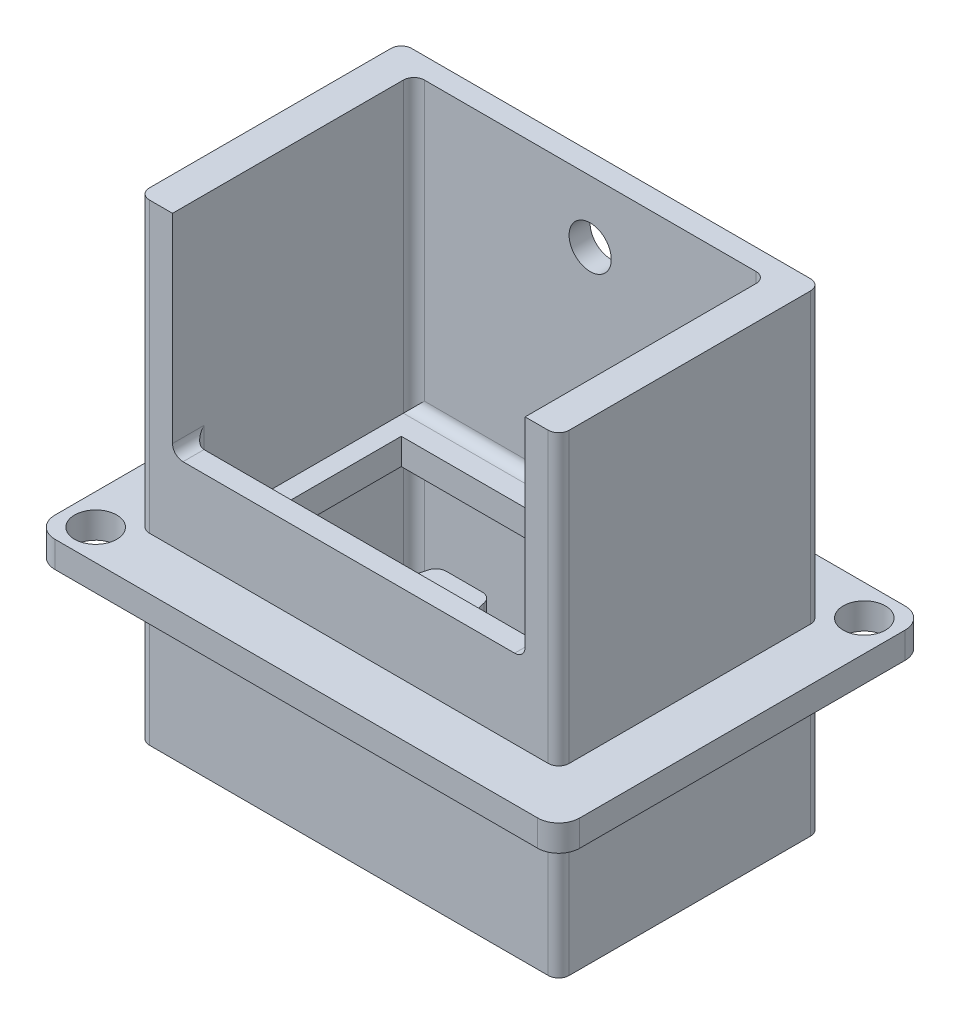
SolidWorks part; units mm, degrees
ref_plane "Front Plane" through (0, 0, 0) normal (0, 0, 1) x (1, 0, 0)
ref_plane "Top Plane" through (0, 0, 0) normal (0, 1, 0) x (1, 0, 0)
ref_plane "Right Plane" through (0, 0, 0) normal (1, 0, 0) x (0, 0, -1)
sketch "Sketch1" plane through (0, 0, 0) normal (0, 1, 0) x (1, 0, 0)
  line L0 (0, 22.225) -> (0, -22.225) construction
  line L1 (-31.75, -22.225) -> (31.75, -22.225)
  line L2 (-31.75, -22.225) -> (-31.75, 22.225)
  line L3 (-31.75, 22.225) -> (31.75, 22.225)
  line L4 (31.75, -22.225) -> (31.75, 22.225)
  line L5 (-31.75, -22.225) -> (31.75, 22.225) construction
  line L6 (-31.75, 22.225) -> (31.75, -22.225) construction
  line L7 (-11.5843, -9.525) -> (-11.176, -9.525)
  line L8 (-19.05, -4.0146) -> (-19.05, 9.525)
  line L9 (-19.05, 9.525) -> (19.05, 9.525)
  line L10 (19.05, -4.0146) -> (19.05, 9.525)
  line L11 (-19.05, -9.525) -> (19.05, 9.525) construction
  line L12 (-19.05, 9.525) -> (19.05, -9.525) construction
  line L13 (3.302, 9.525) -> (3.302, -9.525) construction
  line L14 (-3.302, 9.525) -> (-3.302, -9.525) construction
  line L15 (-19.05, 1.143) -> (19.05, 1.143) construction
  line L16 (-3.302, -1.905) -> (3.302, -1.905)
  line L17 (-11.176, 9.525) -> (-11.176, -9.525) construction
  line L18 (11.176, 9.525) -> (11.176, -9.525) construction
  line L20 (11.176, -9.525) -> (13.6071, -9.525)
  arc A1 (3.302, -1.905) -> (19.05, -4.0146) centre (11.3802, -1.4358) ccw
  arc A2 (-19.05, -4.0146) -> (-3.302, -1.905) centre (-11.3802, -1.4358) ccw
  point P0 (0, 0)
  point P6 (0, 0)
  point P25 (-11.176, 1.143)
  dimension "D1" = 38.1
  dimension "D2" = 19.05
  dimension "D3" = 12.7
  dimension "D4" = 12.7
  dimension "D5" = 15.748
  dimension "D6" = 15.748
  dimension "D7" = 10.668
  dimension "D8" = 11.43
  dimension "D9" = 7.874
  dimension "D10" = 7.874
extrude "Boss-Extrude1" add sketch "Sketch1" along normal blind 3.175
fillet "Fillet3" radius 2.54 4 edges at (31.75, 1.5875, -22.225) (31.75, 1.5875, 22.225) (-31.75, 1.5875, 22.225) (-31.75, 1.5875, -22.225)
sketch "Sketch3" plane through (0, 0, 0) normal (0, -1, 0) x (1, 0, 0)
  line L0 (0, -22.225) -> (0, 22.225) construction
  line L1 (-29.21, -22.225) -> (29.21, -22.225) construction
  line L2 (-29.21, 22.225) -> (29.21, 22.225) construction
  line L3 (31.75, 0) -> (-31.75, 0) construction
  line L4 (31.75, 19.685) -> (31.75, -19.685) construction
  line L5 (-31.75, 19.685) -> (-31.75, -19.685) construction
  line L7 (25.4, 15.875) -> (-25.4, 15.875)
  line L8 (25.4, 15.875) -> (25.4, -15.875)
  line L9 (25.4, -15.875) -> (-25.4, -15.875)
  line L10 (-25.4, 15.875) -> (-25.4, -15.875)
  line L11 (25.4, 15.875) -> (-25.4, -15.875) construction
  line L12 (25.4, -15.875) -> (-25.4, 15.875) construction
  line L13 (21.336, 13.335) -> (-21.336, 13.335)
  line L14 (21.336, 13.335) -> (21.336, -13.335)
  line L15 (21.336, -13.335) -> (-21.336, -13.335)
  line L16 (-21.336, 13.335) -> (-21.336, -13.335)
  line L17 (21.336, 13.335) -> (-21.336, -13.335) construction
  line L18 (21.336, -13.335) -> (-21.336, 13.335) construction
  point P12 (0, 0)
  point P17 (0, 0)
  dimension "D1" = 6.35
  dimension "D2" = 6.35
  dimension "D3" = 2.54
extrude "Boss-Extrude3" add sketch "Sketch3" along normal blind 19.05 and the other way blind 38.1
fillet "Fillet4" radius 1.27 12 edges at (0, 0, 13.335) (-21.336, 0, 0) (0, 0, -13.335) (21.336, 0, 0) (21.336, -9.525, 13.335) (-21.336, -9.525, 13.335) (-21.336, -9.525, -13.335) (21.336, -9.525, -13.335) (25.4, -9.525, -15.875) (25.4, -9.525, 15.875) (-25.4, -9.525, 15.875) (-25.4, -9.525, -15.875)
sketch "Sketch4" plane through (0, 38.1, 0) normal (0, 1, 0) x (1, 0, 0)
  line L0 (-21.336, -13.335) -> (-21.336, -15.875)
  line L1 (25.4, -15.875) -> (-25.4, -15.875) construction
  line L2 (-21.336, -15.875) -> (21.336, -15.875)
  line L3 (21.336, -15.875) -> (21.336, -13.335)
  line L4 (21.336, -13.335) -> (-21.336, -13.335)
extrude "Cut-Extrude1" cut sketch "Sketch4" against normal blind 25.4
fillet "Fillet5" radius 1.27 7 edges at (3.302, 1.5875, 1.905) (-3.302, 1.5875, 1.905) (-21.336, 20.6375, -13.335) (21.336, 20.6375, -13.335) (21.336, 12.7, 14.605) (0, 3.175, -13.335) (-21.336, 12.7, 14.605)
fillet "Fillet6" radius 1.27 3 edges at (0, 3.175, 13.335) (-21.336, 8.5725, 13.335) (21.336, 8.5725, 13.335)
sketch "Sketch5" plane through (0, 0, -15.875) normal (0, 0, -1) x (-1, 0, 0)
  line L0 (0, 3.175) -> (0, 38.1) construction
  line L1 (-25.4, 3.175) -> (25.4, 3.175) construction
  line L2 (25.4, 38.1) -> (-25.4, 38.1) construction
  circle A0 centre (0, 11.557) radius 2.5527
  circle A1 centre (0, 30.607) radius 2.5527
  dimension "D1" = 5.1054
  dimension "D4" = 5.1054
  dimension "D2" = 8.382
  dimension "D3" = 19.05
extrude "Cut-Extrude2" cut sketch "Sketch5" against normal up to next
sketch "Sketch6" plane through (0, 0, 0) normal (0, -1, 0) x (1, 0, 0)
  line L0 (31.0061, -21.4811) -> (25.028, -15.503) construction
  line L1 (-31.0061, 21.4811) -> (-25.028, 15.503) construction
  arc A0 (29.21, -22.225) -> (31.75, -19.685) centre (29.21, -19.685) ccw construction
  arc A1 (24.13, -15.875) -> (25.4, -14.605) centre (24.13, -14.605) ccw construction
  arc A2 (-29.21, 22.225) -> (-31.75, 19.685) centre (-29.21, 19.685) ccw construction
  arc A3 (-24.13, 15.875) -> (-25.4, 14.605) centre (-24.13, 14.605) ccw construction
  circle A4 centre (28.017, -18.492) radius 2.5527
  circle A5 centre (-28.017, 18.492) radius 2.5527
  dimension "D1" = 5.1054
  dimension "D2" = 5.1054
extrude "Cut-Extrude3" cut sketch "Sketch6" against normal up to next
fillet "Fillet7" radius 1.27 4 edges at (25.4, 20.6375, -15.875) (25.4, 20.6375, 15.875) (-25.4, 20.6375, 15.875) (-25.4, 20.6375, -15.875)
